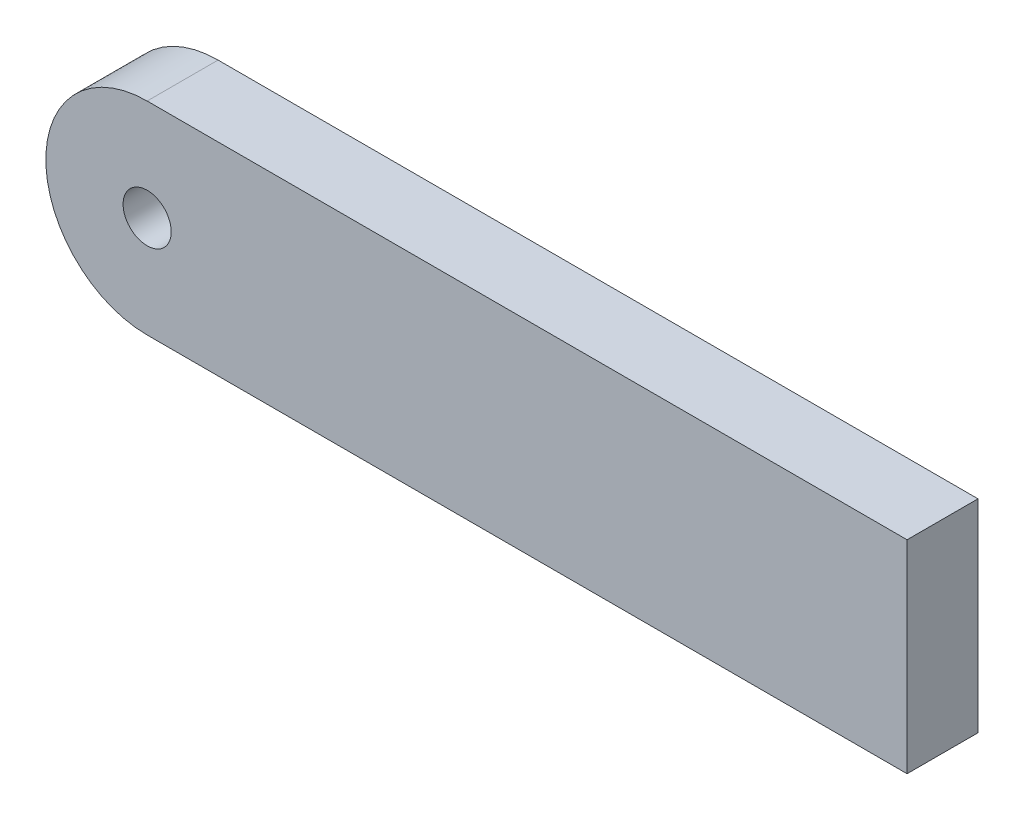
SolidWorks part; units mm, degrees
ref_plane "Front Plane" through (0, 0, 0) normal (0, 0, 1) x (1, 0, 0)
ref_plane "Top Plane" through (0, 0, 0) normal (0, 1, 0) x (1, 0, 0)
ref_plane "Right Plane" through (0, 0, 0) normal (1, 0, 0) x (0, 0, -1)
sketch "Sketch1" plane through (0, 0, 0) normal (0, 0, 1) x (1, 0, 0)
  line L1 (0, 0) -> (300, 0)
  line L2 (0, 0) -> (0, 80)
  line L3 (0, 80) -> (300, 80)
  line L4 (300, 0) -> (300, 80)
  dimension "D1" = 300
  dimension "D2" = 80
extrude "Boss-Extrude1" add sketch "Sketch1" along normal blind 28
sketch "Sketch2" plane through (0, 0, 28) normal (0, 0, 1) x (1, 0, 0)
  line L0 (300, 40) -> (0, 40) construction
  line L1 (300, 0) -> (300, 80) construction
  line L2 (0, -15.4) -> (0, 15.4) construction
  circle A0 centre (0, 40) radius 40
  point P6 (0, 0)
  point P7 (0, 0)
  point P8 (0, 0)
  point P9 (0, 0)
  dimension "D1" = 80
extrude "Boss-Extrude2" add sketch "Sketch2" against normal blind 28
sketch "Sketch3" plane through (0, 0, 28) normal (0, 0, 1) x (1, 0, 0)
  line L0 (-40, 40) -> (300, 40) construction
  line L1 (300, 0) -> (300, 80) construction
  line L2 (0, 80) -> (0, 0) construction
  line L3 (0, -15.4) -> (0, 15.4) construction
  arc A0 (0, 80) -> (0, 0) centre (0, 40) ccw construction
  circle A1 centre (0, 40) radius 9.5
  point P12 (0, 40)
  dimension "D1" = 19
extrude "Cut-Extrude2" cut sketch "Sketch3" against normal through all both
